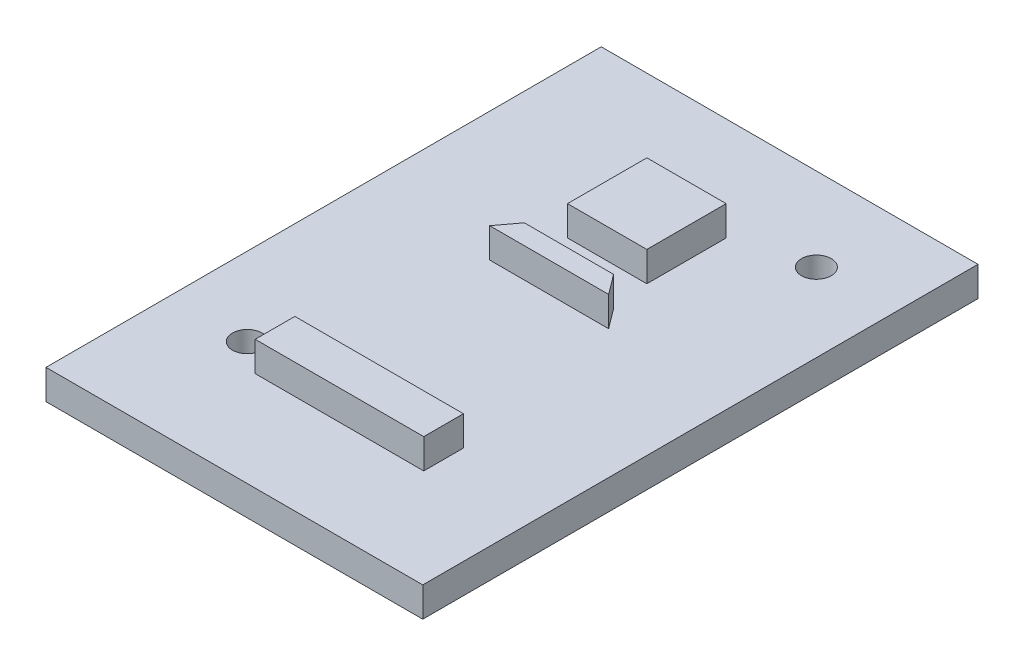
SolidWorks part; units mm, degrees
ref_plane "Front Plane" through (0, 0, 0) normal (0, 0, 1) x (1, 0, 0)
ref_plane "Top Plane" through (0, 0, 0) normal (0, 1, 0) x (1, 0, 0)
ref_plane "Right Plane" through (0, 0, 0) normal (1, 0, 0) x (0, 0, -1)
sketch "Sketch1" plane through (0, 0, 0) normal (0, 1, 0) x (1, 0, 0)
  line L1 (0, 0) -> (13.5, 0)
  line L2 (0, 0) -> (0, 20)
  line L3 (0, 20) -> (13.5, 20)
  line L4 (13.5, 0) -> (13.5, 20)
  dimension "D1" = 20
  dimension "D2" = 13.5
extrude "Boss-Extrude1" add sketch "Sketch1" along normal blind 1.5
sketch "Sketch2" plane through (0, 1.5, 0) normal (0, 1, 0) x (1, 0, 0)
  line L0 (13.5, 20) -> (0, 20) construction
  line L1 (4.75, 17.8) -> (8.75, 17.8)
  line L2 (4.75, 17.8) -> (4.75, 13.8)
  line L3 (4.75, 13.8) -> (8.75, 13.8)
  line L4 (8.75, 17.8) -> (8.75, 13.8)
  line L5 (0, 20) -> (0, 0) construction
  line L7 (13.5, 0) -> (13.5, 20) construction
  line L8 (4.5, 11.8732) -> (9, 11.8732)
  line L9 (3.75, 10.8732) -> (9.75, 10.8732)
  line L10 (4.5, 11.8732) -> (3.75, 10.8732)
  line L11 (9, 11.8732) -> (9.75, 10.8732)
  dimension "D1" = 4
  dimension "D2" = 4
  dimension "D3" = 2.2
  dimension "D4" = 4.75
  dimension "D5" = 4.75
  dimension "D6" = 1
  dimension "D7" = 4.5
  dimension "D8" = 4.5
  dimension "D9" = 3.75
  dimension "D10" = 3.75
extrude "Boss-Extrude2" add sketch "Sketch2" along normal blind 1.5
sketch "Sketch3" plane through (0, 0, 0) normal (0, -1, 0) x (1, 0, 0)
  line L4 (0, -20) -> (0, 0) construction
  line L5 (0, 0) -> (13.5, 0) construction
  line L6 (13.5, 0) -> (13.5, -20) construction
  line L7 (13.5, -20) -> (0, -20) construction
  circle A0 centre (12.3, -18.8) radius 0.75
  circle A1 centre (1.2, -1.2) radius 0.75
  dimension "D1" = 1.5
  dimension "D2" = 1.5
  dimension "D3" = 1.2
  dimension "D4" = 1.2
  dimension "D5" = 1.2
  dimension "D6" = 1.2
extrude "Cut-Extrude1" cut sketch "Sketch3" against normal blind 1.5
sketch "Sketch4" plane through (0, 1.5, 0) normal (0, 1, 0) x (1, 0, 0)
  line L0 (0, 0) -> (13.5, 0) construction
  line L1 (2.8, 0) -> (11.3, 0)
  line L2 (2.8, 0) -> (2.8, 2)
  line L3 (2.8, 2) -> (11.3, 2)
  line L4 (11.3, 0) -> (11.3, 2)
  line L5 (13.5, 0) -> (13.5, 20) construction
  line L6 (0, 20) -> (0, 0) construction
  dimension "D1" = 2.2
  dimension "D2" = 2.8
  dimension "D3" = 2
extrude "Boss-Extrude3" add sketch "Sketch4" along normal blind 1.5
sketch "Sketch5" plane through (0, 1.5, 0) normal (0, 1, 0) x (1, 0, 0)
  line L1 (0, 20) -> (13.5, 20)
  line L2 (0, 20) -> (0, 0)
  line L3 (0, 0) -> (13.5, 0)
  line L4 (13.5, 20) -> (13.5, 0)
  line L5 (-2.75, 23) -> (16.25, 23)
  line L6 (-2.75, 23) -> (-2.75, -5)
  line L7 (-2.75, -5) -> (16.25, -5)
  line L8 (16.25, 23) -> (16.25, -5)
  dimension "D1" = 19
  dimension "D2" = 2.75
  dimension "D3" = 2.75
  dimension "D4" = 3
  dimension "D5" = 5
extrude "Boss-Extrude4" add sketch "Sketch5" against normal blind 1.5
